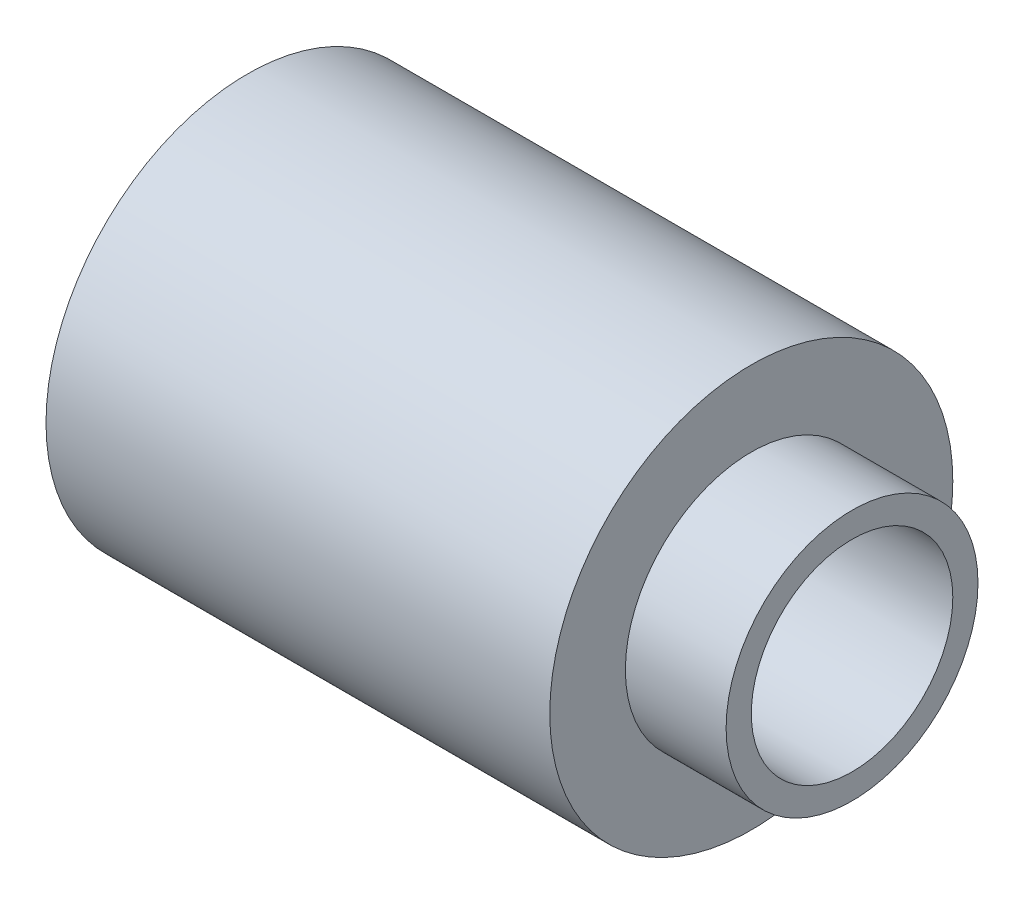
SolidWorks part; units mm, degrees
ref_plane "Front Plane" through (0, 0, 0) normal (0, 0, 1) x (1, 0, 0)
ref_plane "Top Plane" through (0, 0, 0) normal (0, 1, 0) x (1, 0, 0)
ref_plane "Right Plane" through (0, 0, 0) normal (1, 0, 0) x (0, 0, -1)
sketch "Sketch1" plane through (0, 0, 0) normal (1, 0, 0) x (0, 0, -1)
  circle A0 centre (0, 0) radius 4
  circle A1 centre (0, 0) radius 2
  dimension "D1" = 8
  dimension "D2" = 4
extrude "Boss-Extrude1" add sketch "Sketch1" along normal blind 10
sketch "Sketch2" plane through (10, 0, 0) normal (1, 0, 0) x (0, 0, -1)
  circle A0 centre (0, 0) radius 2
  circle A1 centre (0, 0) radius 2.5
  dimension "D1" = 0.5
extrude "Boss-Extrude2" add sketch "Sketch2" along normal blind 2
